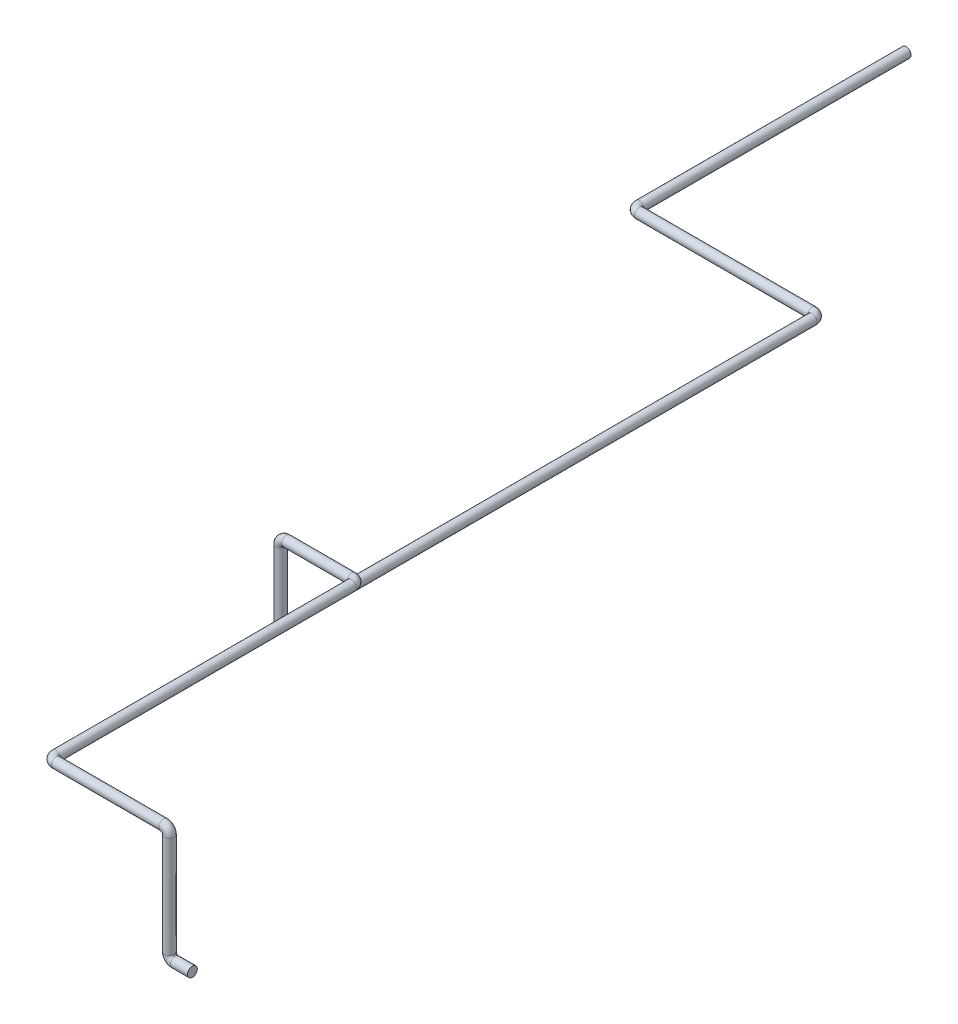
SolidWorks part; units mm, degrees
ref_plane "Alzado" through (0, 0, 0) normal (0, 0, 1) x (1, 0, 0)
ref_plane "Planta" through (0, 0, 0) normal (0, 1, 0) x (1, 0, 0)
ref_plane "Vista lateral" through (0, 0, 0) normal (1, 0, 0) x (0, 0, -1)
sketch "Croquis1" plane through (0, 0, 0) normal (0, 0, 1) x (1, 0, 0)
  circle A0 centre (0, 0) radius 12.7
  dimension "D1" = 25.4
extrude "Saliente-Extruir1" add sketch "Croquis1" along normal blind 10
sketch3d "Croquis3D1"
  line L0 (0, 0, 10) -> (0, 0, 695)
  line L1 (0, 0, 10) -> (0, 0, 0) construction
  line L2 (15, 0, 710) -> (465, 0, 710)
  line L3 (480, 0, 725) -> (480, 0, 2095)
  line L4 (480, 15, 2110) -> (480, 185, 2110)
  line L5 (495, 200, 2110) -> (665, 200, 2110)
  line L6 (680, 200, 2125) -> (680, 200, 2895)
  line L7 (695, 200, 2910) -> (975, 200, 2910)
  line L8 (990, 185, 2910) -> (990, -80, 2910)
  line L9 (1005, -95, 2910) -> (1050, -95, 2910)
  arc A0 (990, -80, 2910) -> (1005, -95, 2910) centre (1005, -80, 2910) ccw
  arc A1 (975, 200, 2910) -> (990, 185, 2910) centre (975, 185, 2910) ccw
  arc A2 (680, 200, 2895) -> (695, 200, 2910) centre (695, 200, 2895) ccw
  arc A3 (665, 200, 2110) -> (680, 200, 2125) centre (665, 200, 2125) ccw
  arc A4 (480, 185, 2110) -> (495, 200, 2110) centre (495, 185, 2110) ccw
  arc A5 (480, 0, 2095) -> (480, 15, 2110) centre (480, 15, 2095) ccw
  arc A6 (465, 0, 710) -> (480, 0, 725) centre (465, 0, 725) ccw
  arc A7 (0, 0, 695) -> (15, 0, 710) centre (15, 0, 695) ccw
  point P14 (990, -95, 2910)
  point P15 (1005, -80, 2925)
  point P18 (990, 200, 2910)
  point P19 (975, 185, 2895)
  point P22 (680, 200, 2910)
  point P23 (695, 215, 2895)
  point P26 (680, 200, 2110)
  point P27 (665, 185, 2125)
  point P30 (480, 200, 2110)
  point P31 (495, 185, 2095)
  point P34 (480, 0, 2110)
  point P35 (465, 15, 2095)
  point P38 (480, 0, 710)
  point P39 (465, -15, 725)
  point P42 (0, 0, 710)
  point P43 (15, 15, 695)
  dimension "D10" = 15
  dimension "D1" = 700
  dimension "D2" = 480
  dimension "D3" = 1400
  dimension "D4" = 200
  dimension "D5" = 200
  dimension "D6" = 800
  dimension "D7" = 310
  dimension "D8" = 295
  dimension "D9" = 60
sketch "Croquis2" plane through (0, 0, 10) normal (0, 0, 1) x (1, 0, 0)
  circle A0 centre (0, 0) radius 12.7
  dimension "D1" = 25.4
sweep "Barrer1" add profiles "Croquis2" path "Croquis3D1"
sketch "Croquis3" plane through (0, 0, 0) normal (0, 0, -1) x (-1, 0, 0)
  line L1 (-0.0463, 12.6751) -> (0.0463, 12.6751)
  line L2 (-0.0463, 12.6751) -> (-0.0463, 12.7249)
  line L3 (-0.0463, 12.7249) -> (0.0463, 12.7249)
  line L4 (0.0463, 12.6751) -> (0.0463, 12.7249)
  line L5 (-0.0463, 12.6751) -> (0.0463, 12.7249) construction
  line L6 (-0.0463, 12.7249) -> (0.0463, 12.6751) construction
  circle A0 centre (0, 0) radius 12.7 construction
  point P0 (0, 12.7)
extrude "Saliente-Extruir2" add sketch "Croquis3" against normal blind 1
